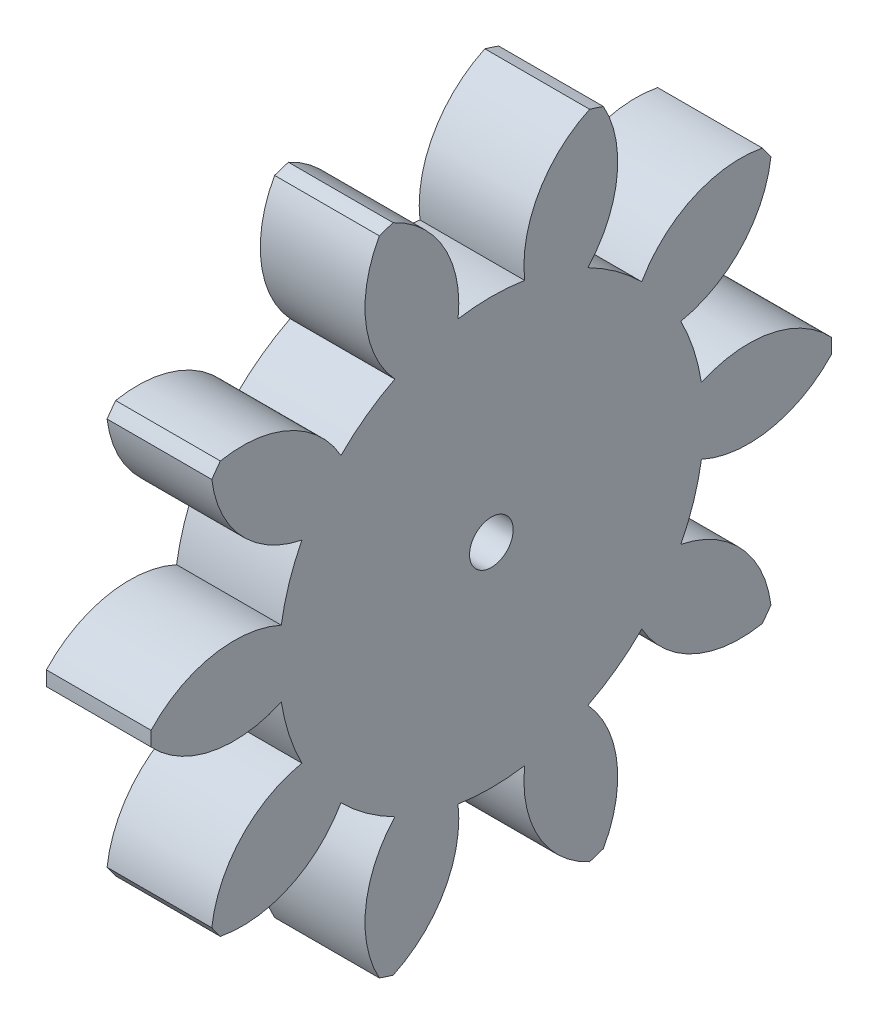
SolidWorks part; units mm, degrees
ref_plane "Plane1" through (0, 0, 0) normal (0, 0, 1) x (1, 0, 0)
ref_plane "Plane2" through (0, 0, 0) normal (0, 1, 0) x (1, 0, 0)
ref_plane "Plane3" through (0, 0, 0) normal (1, 0, 0) x (0, 0, -1)
other "Configuration Table"
sketch "HoldingSke" plane through (0, 0, 0) normal (0, 1, 0) x (1, 0, 0)
  line L0 (0, 0) -> (0.1515, -0.0267)
  line L1 (-15, 0) -> (100, 0) construction
  line L2 (0, 0) -> (-2.1039, 2.3779)
  line L3 (0, 0) -> (-11.863, 4.5341)
  line L4 (0, 0) -> (8.5048, 1.4996)
  line L5 (0, 0) -> (-46.8476, -17.4728)
  line L6 (0, 0) -> (-9.9476, -6.7116)
  line L7 (-2.1039, 2.3779) -> (8.6586, 51.2059)
  line L8 (-76.2, 54.61) -> (-75.7, 54.61)
  line L9 (-71.009, 38.7566) -> (-53.1078, 45.2721)
  line L10 (-76.2, 71.12) -> (104.1128, 71.12)
  line L11 (0, 0) -> (-12, 0)
  line L12 (-76.2, 101.6) -> (-75.981, 101.6)
  line L13 (24.9733, 27.94) -> (52.9518, 28.4284)
  line L14 (24.9733, 27.94) -> (24.9743, 27.94)
  line L15 (24.9733, 27.94) -> (100.4006, 29.5858)
  line L16 (-63.627, -6.5) -> (-12.827, -6.5)
  circle A0 centre (0, 0) radius 1.5
  circle A1 centre (0, 0) radius 24.374
  circle A2 centre (0, 0) radius 37.5
  circle A3 centre (0, 0) radius 1.5
  dimension "MHD" = 48.748
  dimension "Hub_dia" = 75
  dimension "Bore" = 3
  dimension "MBD" = 3
  dimension "Num_teeth" = 10
  dimension "Pitch" = 0.1538
  dimension "Overall_len" = 50
  dimension "Show_teeth" = 10
  dimension "Thickness" = 12
  dimension "OAL" = 50.0001
  dimension "T_dim" = 0.5
  dimension "Ap" = 20
  dimension "H" = 19.05
  dimension "Pitch_radius" = 180.3128
  dimension "Width" = 12
  dimension "Backlash" = 0.219
  dimension "Addendum_fac" = 1
  dimension "Dedendum_fac" = 1.25
  dimension "Clearance_fac" = 0.25
  dimension "Dedendum_add" = 0.001
  dimension "Module" = 6.5
sketch "BasProSke" plane through (0, 0, 0) normal (0, 1, 0) x (1, 0, 0)
  line L0 (-10, 0) -> (60, 0) construction
  line L1 (0, 0) -> (0, 39)
  line L2 (0, 0) -> (12, 0)
  line L3 (12, 0) -> (12, 39)
  line L4 (12, 39) -> (0, 39)
  dimension "Thickness" = 12
  dimension "Diameter" = 78
revolve "Base-Revolve" add sketch "BasProSke" angle 360 about L0
sketch "TooCutSke" plane through (0, 0, 0) normal (1, 0, 0) x (0, 0, -1)
  line L1 (0, 0) -> (0, 107) construction
  line L2 (0, 0) -> (-5.4666, 32.0369) construction
  line L3 (0, 0) -> (-19.8749, 61.1686) construction
  line L4 (-5.4666, 32.0369) -> (-9.9374, 30.5843) construction
  arc A0 (3.8158, 24.0735) -> (-3.8158, 24.0735) centre (0, 0) ccw
  arc A1 (11.2922, 37.356) -> (-11.2922, 37.356) centre (0, 0) ccw
  circle A2 centre (0, 0) radius 32.5 construction
  circle A3 centre (0, 0) radius 30.54 construction
  arc A4 (-3.8158, 24.0735) -> (-11.2922, 37.356) centre (-16.7318, 25.5488) ccw
  arc A5 (11.2922, 37.356) -> (3.8158, 24.0735) centre (16.7318, 25.5488) ccw
  dimension "Root_dia" = 48.748
  dimension "Overcut_dia" = 78.0508
  dimension "Pitch_dia" = 65
  dimension "Base_dia" = 61.08
  dimension "Flank_rad" = 13
  dimension "Half_ang" = 18
  dimension "Half_CT" = 4.7009
extrude "ToothCut" cut sketch "TooCutSke" along normal through all
fillet "Breaks" [suppressed] radius 0.13
fillet "RootFillets" [suppressed] radius 1.626
pattern_circular "TeethCuts" count 10 every 36 about axis through (-10, 0, 0) along (1, 0, 0) of "ToothCut", "RootFillets", "Breaks"
sketch "HubNeaOneSke" plane through (0, 0, 0) normal (-1, 0, 0) x (0, 0, 1)
  circle A0 centre (0, 0) radius 24.374
  dimension "Diameter" = 48.748
extrude "HubNearOne" [suppressed] add sketch "HubNeaOneSke" along normal blind 38.0001
sketch "HubNeaBotSke" plane through (0, 0, 0) normal (-1, 0, 0) x (0, 0, 1)
  circle A0 centre (0, 0) radius 24.374
  dimension "Diameter" = 48.748
extrude "HubNearBoth" [suppressed] add sketch "HubNeaBotSke" along normal blind 19
ref_plane "FarPln" through (12, 0, 0) normal (1, 0, 0) x (0, 0, -1)
sketch "HubFarSke" plane through (12, 0, 0) normal (1, 0, 0) x (0, 0, -1)
  circle A0 centre (0, 0) radius 24.374
  dimension "Diameter" = 48.748
extrude "HubFar" [suppressed] add sketch "HubFarSke" along normal blind 19
sketch "BorSke" plane through (0, 0, 0) normal (1, 0, 0) x (0, 0, -1)
  circle A0 centre (0, 0) radius 1.5
  dimension "Diameter" = 3
extrude "Bore" cut sketch "BorSke" along normal mid plane 100.0001
sketch "KeySke" plane through (0, 0, 0) normal (1, 0, 0) x (0, 0, -1)
  line L0 (-0.6, 0) -> (-0.6, 2)
  line L1 (-0.6, 2) -> (0.6, 2)
  line L2 (0.6, 2) -> (0.6, 0)
  line L3 (0, 0) -> (0, 34) construction
  line L4 (-0.6, 0) -> (0.6, 0)
  dimension "Offset" = 2
extrude "Keyway" [suppressed] cut sketch "KeySke" along normal mid plane 100.0001
pattern_circular "Keyway2" [suppressed] count 2 every 90 about axis through (-10, 0, 0) along (1, 0, 0)
sketch "Croquis1" plane through (12, 0, 0) normal (1, 0, 0) x (0, 1, 0)
  circle A0 centre (0, 0) radius 2.5
  dimension "D1" = 5
extrude "Cortar-Extruir1" cut sketch "Croquis1" against normal through all
equation "' \"Module@HoldingSke\" = 6.35"
equation "' \"Num_teeth@HoldingSke\" = 12"
equation "' \"Ap@HoldingSke\" =  20"
equation "' \"Ap@HoldingSke\" = 20"
equation "' \"Width@HoldingSke\" = 0.5 * 25.4"
equation "' \"Hub_dia@HoldingSke\"= 1 * 25.4"
equation "' \"Hub_dia@HoldingSke\" = 1 * 25.4"
equation "' \"Overall_len@HoldingSke\" = 1.0 * 25.4"
equation "' \"Bore@HoldingSke\" = 0.75 * 25.4"
equation "' \"T_dim@HoldingSke\" = 0.1 * 25.4"
equation "' \"Width@KeySke\" = 0.25 * 25.4"
equation "' \"Show_teeth@HoldingSke\" = 13"
equation "' \"Backlash@HoldingSke\" = 0.009 * 25.4"
equation "' \"Addendum_fac@HoldingSke\" = 1.0"
equation "' \"Dedendum_fac@HoldingSke\" = 1.25"
equation "' \"Dedendum_add@HoldingSke\" = 0.00005 * 25.4"
equation "' \"Clearance_fac@HoldingSke\" = 0.25"
equation "\"Pitch@HoldingSke\" = 1 / \"Module@HoldingSke\""
equation "\"Overcut_dia@TooCutSke\" = (\"Num_teeth@HoldingSke\" + 2 * \"Addendum_fac@HoldingSke\") / \"Pitch@HoldingSke\" + 0.002 * 25.4"
equation "\"Pitch_dia@TooCutSke\" = \"Num_teeth@HoldingSke\" / \"Pitch@HoldingSke\""
equation "\"Base_dia@TooCutSke\" = \"Num_teeth@HoldingSke\" / \"Pitch@HoldingSke\" * cos((\"Ap@HoldingSke\"  * 3.14159265 / 180))"
equation "\"Root_dia@TooCutSke\" = (\"Num_teeth@HoldingSke\" + 2) / \"Pitch@HoldingSke\" - 2 * (\"Addendum_fac@HoldingSke\" + \"Dedendum_fac@HoldingSke\") / \"Pitch@HoldingSke\" - \"Dedendum_add@HoldingSke\" * 2"
equation "\"Half_ang@TooCutSke\" = 180 / \"Num_teeth@HoldingSke\""
equation "\"Half_CT@TooCutSke\" = \"Num_teeth@HoldingSke\" / \"Pitch@HoldingSke\" * sin((3.14159265 / 2 / \"Num_teeth@HoldingSke\")) / 2 - 7 * \"Backlash@HoldingSke\" / 4"
equation "\"Flank_rad@TooCutSke\" = \"Num_teeth@HoldingSke\" / \"Pitch@HoldingSke\" / 5"
equation "\"Radius@RootFillets\" = \"Clearance_fac@HoldingSke\" / \"Pitch@HoldingSke\" + \"Dedendum_add@HoldingSke\""
equation "\"Break_rad@Breaks\" = 0.02 / \"Pitch@HoldingSke\""
equation "\"Thickness@HoldingSke\" = \"Width@HoldingSke\""
equation "\"OAL@HoldingSke\" = \"Thickness@HoldingSke\""
equation "\"MHD@HoldingSke\" = (\"Num_teeth@HoldingSke\" + 2) / \"Pitch@HoldingSke\" - 2 * (\"Addendum_fac@HoldingSke\" + \"Dedendum_fac@HoldingSke\")  / \"Pitch@HoldingSke\" - \"Dedendum_add@HoldingSke\" * 2"
equation "\"MBD@HoldingSke\" = (\"Num_teeth@HoldingSke\" + 2) / \"Pitch@HoldingSke\" - 2 * (\"Addendum_fac@HoldingSke\" + \"Dedendum_fac@HoldingSke\")  / \"Pitch@HoldingSke\" - \"Dedendum_add@HoldingSke\" * 2 - 0.002 * 25.4"
equation "\"MHD@HoldingSke\" = ((sgn( \"MHD@HoldingSke\" - \"Hub_dia@HoldingSke\" )-1)*( \"MHD@HoldingSke\" - \"Hub_dia@HoldingSke\" ))/-2+ \"Hub_dia@HoldingSke\""
equation "\"MBD@HoldingSke\" = ((sgn( \"MBD@HoldingSke\" - \"Bore@HoldingSke\" )-1)*( \"MBD@HoldingSke\" - \"Bore@HoldingSke\" ))/-2+ \"Bore@HoldingSke\""
equation "\"OAL@HoldingSke\" = ((sgn( \"OAL@HoldingSke\" - \"Overall_len@HoldingSke\" )+1)*( \"OAL@HoldingSke\" - \"Overall_len@HoldingSke\" ))/2 + \"Overall_len@HoldingSke\" + 0.000002 * 25.4"
equation "\"Num_teeth@TeethCuts\" = int( \"Show_teeth@HoldingSke\" ) + 1"
equation "\"Num_teeth@TeethCuts\" = ((sgn( \"Num_teeth@TeethCuts\" - \"Num_teeth@HoldingSke\" )-1)*( \"Num_teeth@TeethCuts\" - \"Num_teeth@HoldingSke\" ))/-2+ \"Num_teeth@HoldingSke\""
equation "\"Num_teeth@TeethCuts\" = ((sgn( \"Num_teeth@TeethCuts\" - 2.0)+1)*( \"Num_teeth@TeethCuts\" - 2.0))/2 +2.0"
equation "\"Angle@TeethCuts\" = 360.0 / \"Num_teeth@HoldingSke\""
equation "\"Diameter@BasProSke\" = (\"Num_teeth@HoldingSke\" + 2 * \"Addendum_fac@HoldingSke\") / \"Pitch@HoldingSke\""
equation "\"Thickness@BasProSke\"  = \"Thickness@HoldingSke\""
equation "' \"Fillet_rad@BasProSke\" =  \"Thickness@HoldingSke\" * 0.05"
equation "' \"Fillet_rad@BasProSke\" = \"Thickness@HoldingSke\" * 0.05"
equation "\"MHD@HoldingSke\" = ((sgn( \"MHD@HoldingSke\" - \"Root_dia@TooCutSke\" )-1)*( \"MHD@HoldingSke\" - \"Root_dia@TooCutSke\" ))/-2+ \"Root_dia@TooCutSke\""
equation "\"Diameter@HubNeaOneSke\" = \"MHD@HoldingSke\""
equation "\"Length@HubNearOne\" = \"OAL@HoldingSke\" - \"Thickness@BasProSke\""
equation "\"Diameter@HubNeaBotSke\" = \"MHD@HoldingSke\""
equation "\"Length@HubNearBoth\" = ( \"OAL@HoldingSke\" - \"Thickness@BasProSke\" ) / 2.0"
equation "\"Thickness@FarPln\" = \"Thickness@BasProSke\""
equation "\"Diameter@HubFarSke\" = \"MHD@HoldingSke\""
equation "\"Length@HubFar\" = ( \"OAL@HoldingSke\" - \"Thickness@BasProSke\" ) / 2.0"
equation "\"Diameter@BorSke\" = \"MBD@HoldingSke\""
equation "\"D1@Bore\" = \"OAL@HoldingSke\" * 2.0"
equation "\"D1@Keyway\" = \"OAL@HoldingSke\" * 2.0"
equation "\"Offset@KeySke\" = \"T_dim@HoldingSke\" + \"MBD@HoldingSke\" / 2.0"
